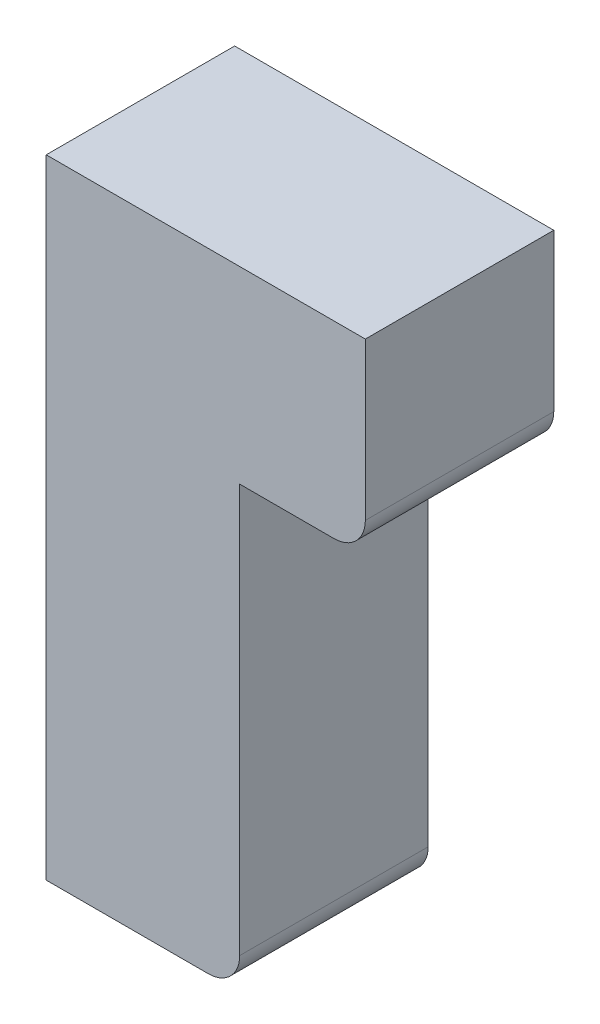
SolidWorks part; units mm, degrees
ref_plane "Front Plane" through (0, 0, 0) normal (0, 0, 1) x (1, 0, 0)
ref_plane "Top Plane" through (0, 0, 0) normal (0, 1, 0) x (1, 0, 0)
ref_plane "Right Plane" through (0, 0, 0) normal (1, 0, 0) x (0, 0, -1)
sketch "Sketch1" plane through (0, 0, 0) normal (0, 0, 1) x (1, 0, 0)
  line L0 (-6.4452, 7.1392) -> (-1.3652, 7.1392)
  line L1 (-1.3652, 7.1392) -> (-1.3652, 4.1392)
  line L2 (-1.3652, 4.1392) -> (-3.3652, 4.1392)
  line L3 (-3.3652, 4.1392) -> (-3.3652, -2.8608)
  line L4 (-3.3652, -2.8608) -> (-6.4452, -2.8608)
  line L5 (-6.4452, -2.8608) -> (-6.4452, 7.1392)
  dimension "D1" = 3.08
  dimension "D2" = 2
  dimension "D3" = 3
  dimension "D4" = 10
extrude "Boss-Extrude1" add sketch "Sketch1" along normal blind 3
fillet "Fillet1" radius 0.5 1 edges at (-3.3652, -2.8608, 1.5)
fillet "Fillet3" radius 0.5 1 edges at (-1.3652, 4.1392, 1.5)
